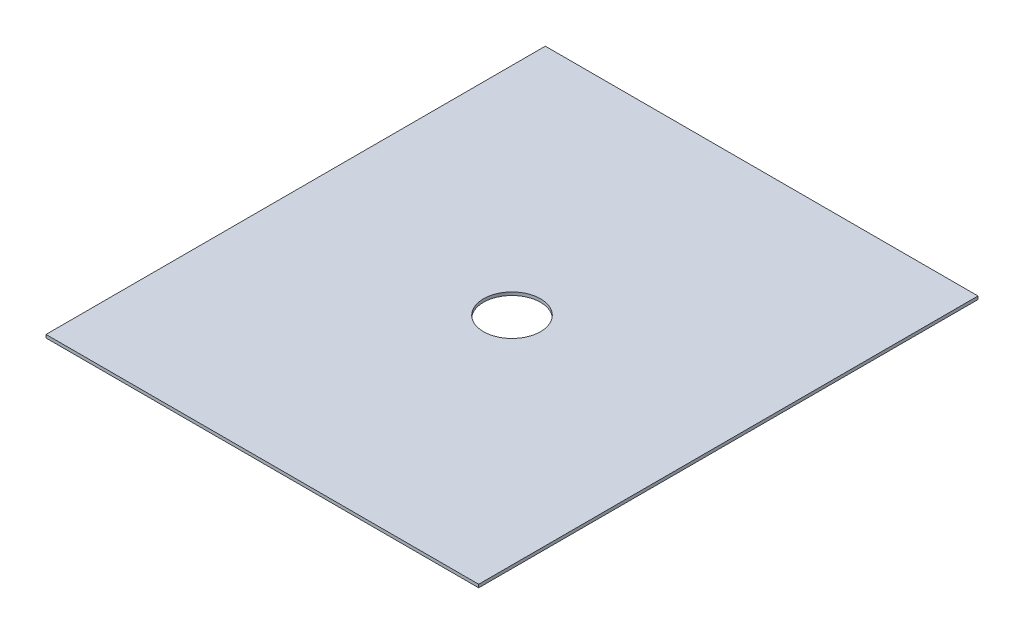
SolidWorks part; units mm, degrees
ref_plane "Front Plane" through (0, 0, 0) normal (0, 0, 1) x (1, 0, 0)
ref_plane "Top Plane" through (0, 0, 0) normal (0, 1, 0) x (1, 0, 0)
ref_plane "Right Plane" through (0, 0, 0) normal (1, 0, 0) x (0, 0, -1)
sketch "Sketch1" plane through (0, 0, 0) normal (0, 1, 0) x (1, 0, 0)
  line L1 (-138.65, 160) -> (138.65, 160)
  line L2 (-138.65, 160) -> (-138.65, -160)
  line L3 (-138.65, -160) -> (138.65, -160)
  line L4 (138.65, 160) -> (138.65, -160)
  line L5 (-138.65, 160) -> (138.65, -160) construction
  line L6 (-138.65, -160) -> (138.65, 160) construction
  point P0 (0, 0)
  dimension "D1" = 277.3
  dimension "D2" = 320
extrude "Top" add sketch "Sketch1" along normal blind 2
sketch "Sketch2" plane through (0, 2, 0) normal (0, 1, 0) x (1, 0, 0)
  circle A0 centre (0, 0) radius 18.2815
extrude "Cut-Extrude1" cut sketch "Sketch2" against normal blind 10
